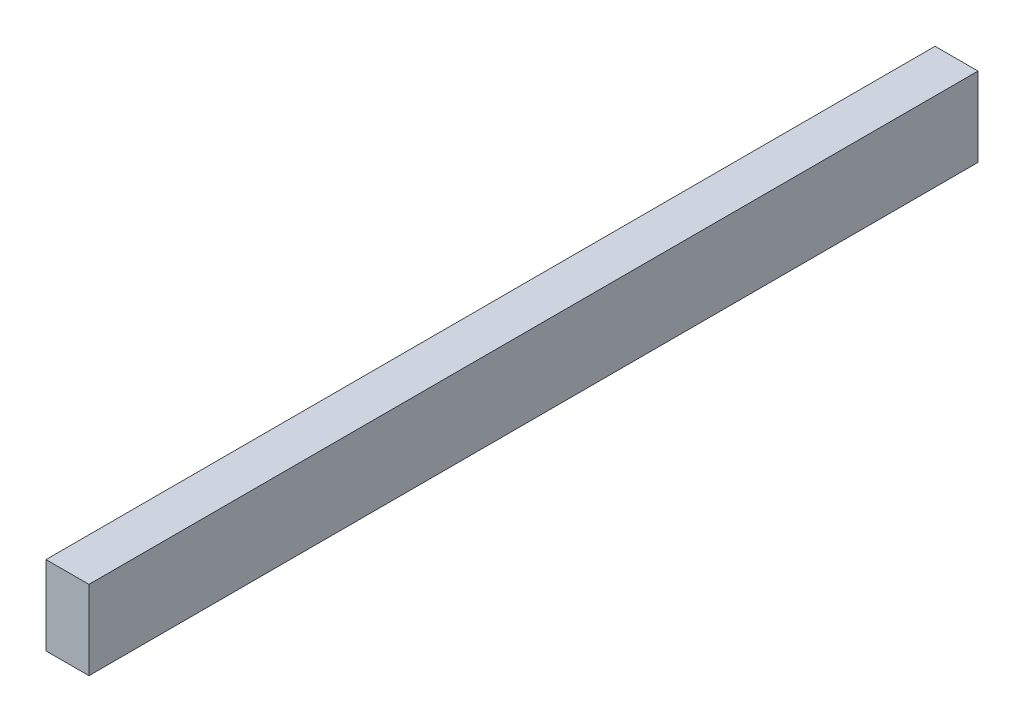
SolidWorks part; units mm, degrees
ref_plane "Front Plane" through (0, 0, 0) normal (0, 0, 1) x (1, 0, 0)
ref_plane "Top Plane" through (0, 0, 0) normal (0, 1, 0) x (1, 0, 0)
ref_plane "Right Plane" through (0, 0, 0) normal (1, 0, 0) x (0, 0, -1)
sketch "Sketch1" plane through (0, 0, 0) normal (1, 0, 0) x (0, 0, -1)
  line L0 (-23.7476, 0) -> (48.7524, 0)
  line L1 (39.875, 0) -> (-39.875, 0) construction
  line L2 (48.7524, 0) -> (48.7524, 6.4528)
  line L3 (48.7524, 6.4528) -> (-23.7476, 6.4528)
  line L4 (-23.7476, 6.4528) -> (-23.7476, 0)
extrude "Boss-Extrude1" add sketch "Sketch1" along normal blind 3.5
